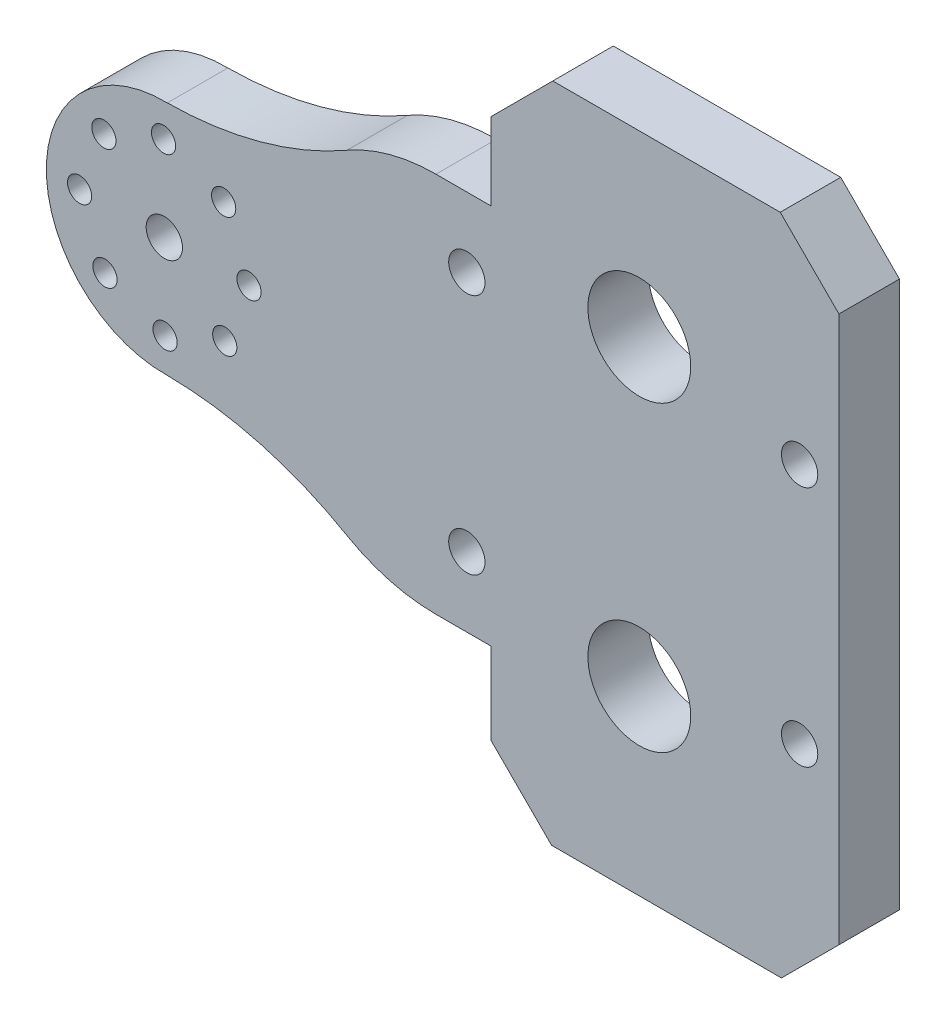
SolidWorks part; units mm, degrees
ref_plane "Front Plane" through (0, 0, 0) normal (0, 0, 1) x (1, 0, 0)
ref_plane "Top Plane" through (0, 0, 0) normal (0, 1, 0) x (1, 0, 0)
ref_plane "Right Plane" through (0, 0, 0) normal (1, 0, 0) x (0, 0, -1)
sketch "Sketch1" plane through (0, 0, 0) normal (0, 0, 1) x (1, 0, 0)
  line L30 (45.2509, -25.2077) -> (50.0009, -20.4577)
  line L31 (50.0009, -20.4577) -> (50.0009, 24.6887)
  line L32 (50.0009, 24.6887) -> (45.1474, 29.5423)
  line L33 (45.1474, 29.5423) -> (26.3545, 29.5423)
  line L34 (26.3545, 29.5423) -> (21.2509, 24.4387)
  line L35 (21.2509, 24.4387) -> (21.2509, 18.0423)
  line L36 (21.2509, 18.0423) -> (20.4081, 18.0423)
  line L37 (20.4081, 18.0423) -> (16.7009, 18.0423)
  line L38 (-5.4991, 12.0433) -> (-5.4991, 12.0391)
  line L39 (-5.4991, -7.4545) -> (-5.4991, -7.4587)
  line L40 (16.7009, -13.4577) -> (20.4081, -13.4577)
  line L41 (20.4081, -13.4577) -> (21.2509, -13.4577)
  line L42 (21.2509, -13.4577) -> (21.2509, -20.2077)
  line L43 (21.2509, -20.2077) -> (26.2509, -25.2077)
  line L44 (26.2509, -25.2077) -> (45.2509, -25.2077)
  arc A10 (16.7009, 18.0423) -> (9.3423, 16.0756) centre (16.7009, 3.2923) ccw
  arc A11 (-5.4991, 12.0433) -> (9.3423, 16.0756) centre (-5.7491, 42.2923) ccw
  arc A12 (-5.4991, 12.0391) -> (-5.4991, -7.4545) centre (-5.7491, 2.2923) ccw
  arc A13 (9.3423, -11.491) -> (-5.4991, -7.4587) centre (-5.7491, -37.7077) ccw
  arc A14 (9.3423, -11.491) -> (16.7009, -13.4577) centre (16.7009, 1.2923) ccw
  circle A25 centre (46.7509, -7.7077) radius 1.5
  circle A26 centre (46.7509, 12.2923) radius 1.5
  circle A27 centre (33.5009, 14.7923) radius 4.25
  circle A28 centre (33.5009, -10.2077) radius 4.25
  circle A29 centre (19.2509, 12.2923) radius 1.5
  circle A30 centre (19.2509, -7.7077) radius 1.5
  circle A31 centre (-5.7491, 2.2923) radius 1.5
  circle A32 centre (1.2509, 2.3547) radius 1
  circle A33 centre (-0.7554, -2.6131) radius 1
  circle A34 centre (-5.6866, -4.7077) radius 1
  circle A35 centre (-10.6545, -2.7014) radius 1
  circle A36 centre (-12.7491, 2.2298) radius 1
  circle A37 centre (-10.7428, 7.1977) radius 1
  circle A38 centre (-5.8115, 9.2923) radius 1
  circle A39 centre (-0.8437, 7.286) radius 1
extrude "Boss-Extrude2" add sketch "Sketch1" along normal blind 5
